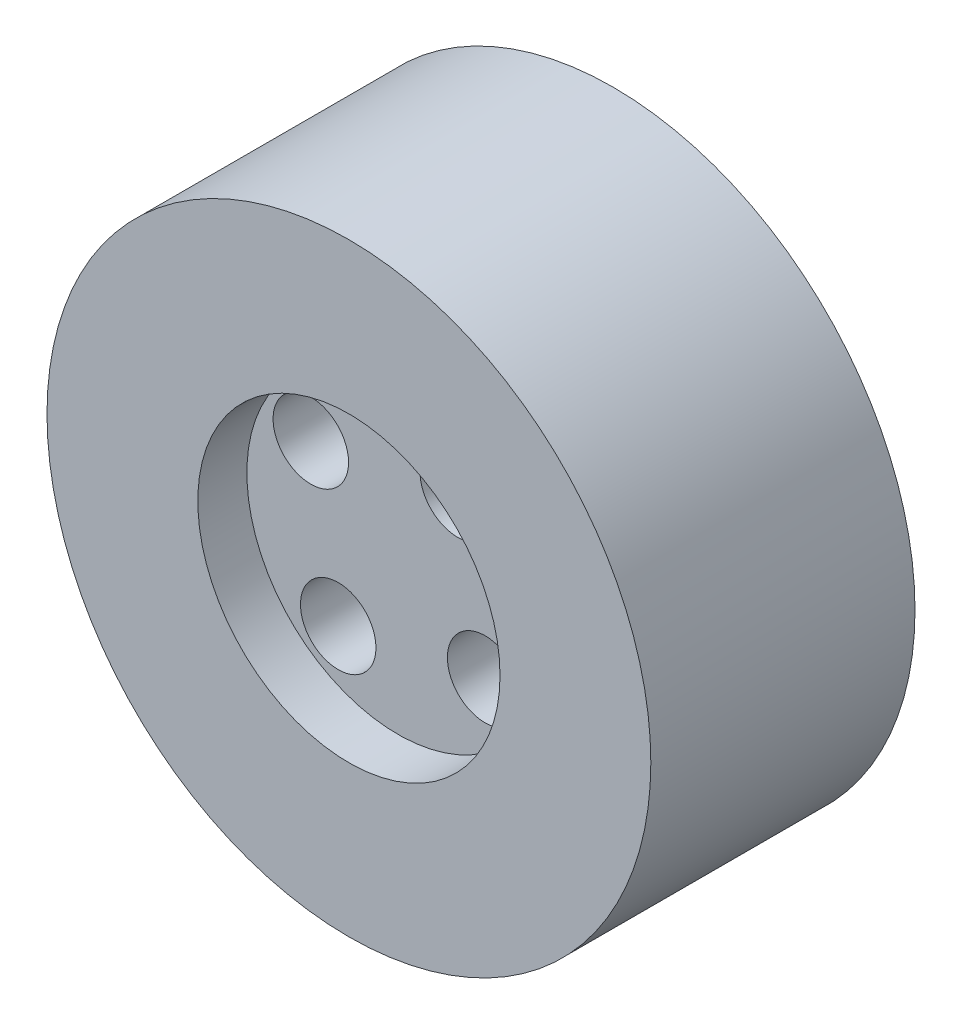
SolidWorks part; units mm, degrees
ref_plane "Front Plane" through (0, 0, 0) normal (0, 0, 1) x (1, 0, 0)
ref_plane "Top Plane" through (0, 0, 0) normal (0, 1, 0) x (1, 0, 0)
ref_plane "Right Plane" through (0, 0, 0) normal (1, 0, 0) x (0, 0, -1)
sketch "Sketch1" plane through (0, 0, 0) normal (0, 0, 1) x (1, 0, 0)
  circle A0 centre (0, 0) radius 40
extrude "Boss-Extrude1" add sketch "Sketch1" along normal blind 35
sketch "Sketch2" plane through (0, 0, 35) normal (0, 0, 1) x (1, 0, 0)
  circle A0 centre (0, 0) radius 20.02
extrude "Cut-Extrude2" cut sketch "Sketch2" against normal blind 6.5
sketch "Sketch3" plane through (0, 0, 35) normal (0, 0, 1) x (1, 0, 0)
  circle A0 centre (-11.5459, 7.9179) radius 5
  point P2 (0, 0)
  dimension "D1" = 14
extrude "Cut-Extrude3" cut sketch "Sketch3" against normal through all
pattern_circular "CirPattern1" count 4 over 360 about axis through (0, 0, 0) along (0, 0, 1) of "Cut-Extrude3"
